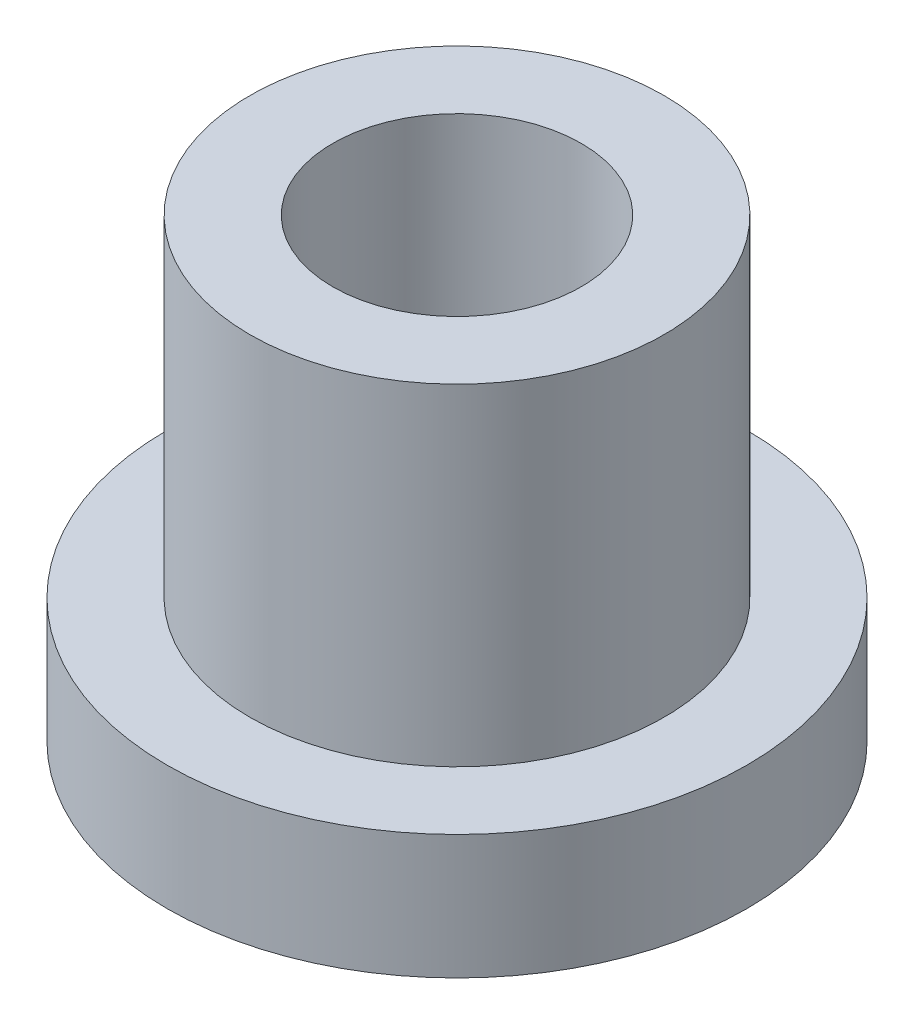
SolidWorks part; units mm, degrees
material "Custom Plastic"
ref_plane "Ön Düzlem" through (0, 0, 0) normal (0, 0, 1) x (1, 0, 0)
ref_plane "Üst Düzlem" through (0, 0, 0) normal (0, 1, 0) x (1, 0, 0)
ref_plane "Sağ Düzlem" through (0, 0, 0) normal (1, 0, 0) x (0, 0, -1)
sketch "Çizim3" plane through (0, 0, 0) normal (0, 1, 0) x (1, 0, 0)
  circle A0 centre (0, 0) radius 3
  circle A1 centre (0, 0) radius 7
  dimension "D1" = 6
  dimension "D2" = 14
extrude "Yükseklik-Ekstrüzyon2" add sketch "Çizim3" along normal blind 3
sketch "Çizim4" plane through (0, 3, 0) normal (0, 1, 0) x (1, 0, 0)
  circle A0 centre (0, 0) radius 5
  circle A1 centre (0, 0) radius 3
  dimension "D1" = 10
extrude "Yükseklik-Ekstrüzyon3" add sketch "Çizim4" along normal blind 8
